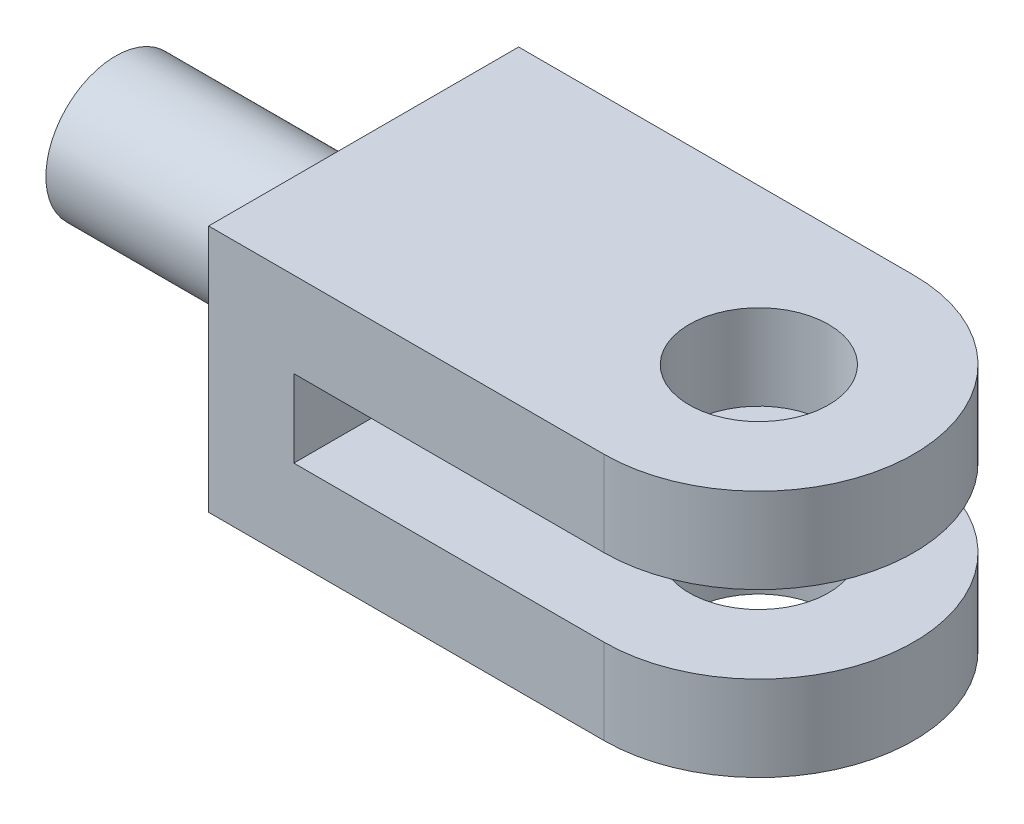
SolidWorks part; units mm, degrees
ref_plane "Front Plane" through (0, 0, 0) normal (0, 0, 1) x (1, 0, 0)
ref_plane "Top Plane" through (0, 0, 0) normal (0, 1, 0) x (1, 0, 0)
ref_plane "Right Plane" through (0, 0, 0) normal (1, 0, 0) x (0, 0, -1)
sketch "Sketch1" plane through (0, 0, 0) normal (1, 0, 0) x (0, 0, -1)
  line L1 (-20, 16) -> (20, 16)
  line L2 (-20, 16) -> (-20, -16)
  line L3 (-20, -16) -> (20, -16)
  line L4 (20, 16) -> (20, -16)
  line L5 (-20, 16) -> (20, -16) construction
  line L6 (-20, -16) -> (20, 16) construction
  circle A0 centre (0, 0) radius 9
  point P0 (0, 0)
  dimension "D1" = 18
  dimension "D2" = 40
  dimension "D3" = 32
extrude "Boss-Extrude1" add sketch "Sketch1" along normal blind 32 contours A0
sketch "Sketch2" plane through (32, 0, 0) normal (1, 0, 0) x (0, 0, -1)
  line L1 (-20, 16) -> (20, 16)
  line L2 (-20, 16) -> (-20, -16)
  line L3 (-20, -16) -> (20, -16)
  line L4 (20, 16) -> (20, -16)
  line L5 (-20, 16) -> (20, -16) construction
  line L6 (-20, -16) -> (20, 16) construction
  point P0 (0, 0)
  dimension "D1" = 32
  dimension "D2" = 40
extrude "Boss-Extrude2" add sketch "Sketch2" along normal blind 11
sketch "Sketch3" plane through (0, -16, 0) normal (0, -1, 0) x (-1, 0, 0)
  line L0 (-83, 20) -> (-43, 20)
  line L1 (-83, -20) -> (-43, -20)
  arc A0 (-83, 20) -> (-83, -20) centre (-83, 0) ccw
  circle A1 centre (-83, 0) radius 9
  dimension "D1" = 40
  dimension "D2" = 18
  dimension "D3" = 40
  dimension "D4" = 40
extrude "Boss-Extrude5" add sketch "Sketch3" against normal blind 11
pattern_linear "LPattern1" count 2 spacing 21 along (0, 1, 0) of "Boss-Extrude5"
